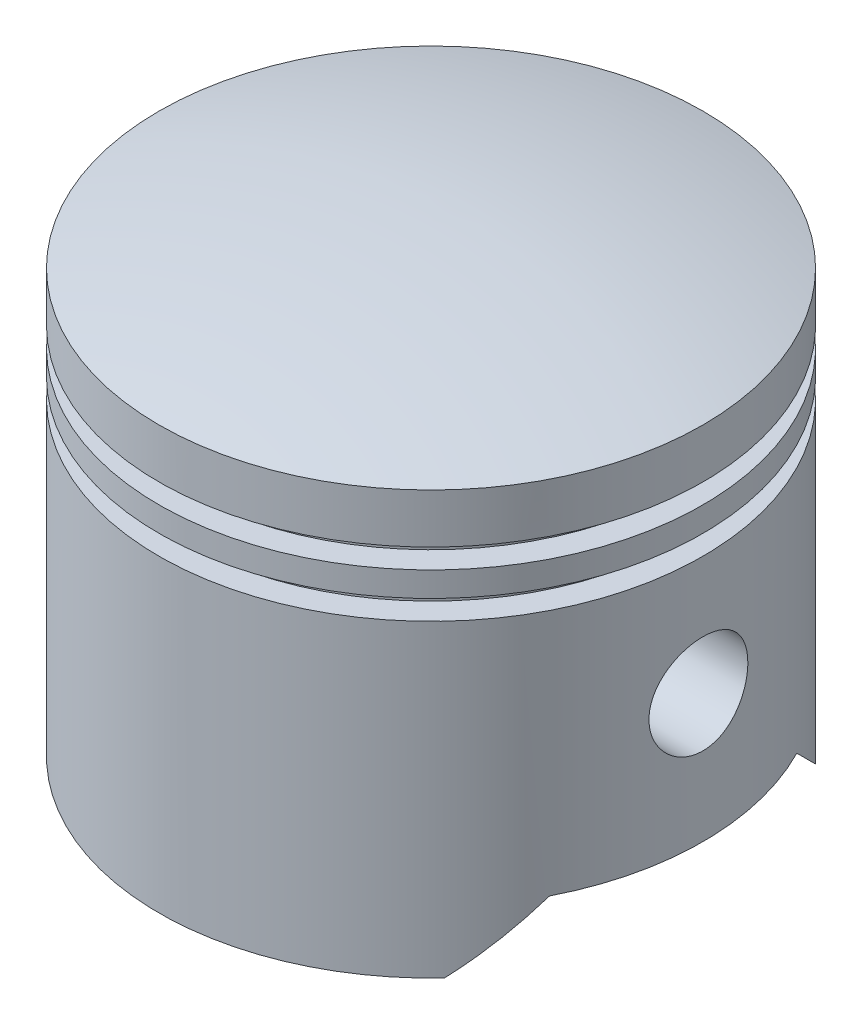
SolidWorks part; units mm, degrees
ref_plane "前视基准面" through (0, 0, 0) normal (0, 0, 1) x (1, 0, 0)
ref_plane "上视基准面" through (0, 0, 0) normal (0, 1, 0) x (1, 0, 0)
ref_plane "右视基准面" through (0, 0, 0) normal (1, 0, 0) x (0, 0, -1)
other "Configuration Table"
sketch "草图1" plane through (0, 0, 0) normal (0, 0, 1) x (1, 0, 0)
  line L0 (0, 40.7414) -> (0, -37.5312) construction
  line L1 (-34.875, 0) -> (35, 0) construction
  line L2 (-22, 9.6331) -> (-22, -15.3669)
  line L3 (-22, -15.3669) -> (0, -15.3669)
  line L4 (-22, 9.6331) -> (-20, 9.6331)
  line L5 (-20, 9.6331) -> (-20, 11.2331)
  line L6 (-20, 11.2331) -> (-22, 11.2331)
  line L7 (-22, 11.2331) -> (-22, 13.2331)
  line L8 (-22, 13.2331) -> (-20, 13.2331)
  line L9 (-20, 13.2331) -> (-20, 14.8331)
  line L10 (-20, 14.8331) -> (-22, 14.8331)
  line L11 (-22, 14.8331) -> (-22, 18.8331)
  line L12 (0, 22) -> (0, -15.3669)
  arc A1 (-22, 18.8331) -> (0, 22) centre (0, -56) cw
  dimension "D6" = 78
  dimension "D1" = 2
  dimension "D2" = 4
  dimension "D3" = 2
  dimension "D4" = 1.6
  dimension "D5" = 1.6
  dimension "D7" = 25
  dimension "D8" = 44
  dimension "D9" = 22
  dimension "D10" = 2
  dimension "D11" = 2
  dimension "D12" = 2
revolve "旋转3" add sketch "草图1" angle 360 about L12
sketch "草图4" plane through (0, 0, 0) normal (1, 0, 0) x (0, 0, -1)
  line L0 (0, 24.7947) -> (0, -19.6691) construction
  line L1 (-15, -15.3669) -> (-10, -10.3669)
  line L2 (-22, -15.3669) -> (22, -15.3669) construction
  line L3 (-10, -10.3669) -> (10, -10.3669)
  line L4 (15, -15.3669) -> (10, -10.3669)
  line L5 (-15, -15.3669) -> (15, -15.3669)
  circle A0 centre (0, 0) radius 4
  point P11 (0, -10.3669)
  dimension "D1" = 8
  dimension "D2" = 30
  dimension "D3" = 45
  dimension "D4" = 5
extrude "切除-拉伸2" cut sketch "草图4" against normal through all both and the other way through all contours A0 | L5 L4 L3 L1
sketch "草图6" plane through (0, -15.3669, 0) normal (0, -1, 0) x (1, 0, 0)
  circle A0 centre (0, 0) radius 20
  dimension "D1" = 40
extrude "切除-拉伸3" cut sketch "草图6" against normal up to surface (5 mm away) up to face at (0, -10.3669, 0)
sketch "草图7" plane through (0, -10.3669, 0) normal (0, -1, 0) x (1, 0, 0)
  line L0 (0, 22.4783) -> (0, -25.2558) construction
  line L3 (-35.2351, 0) -> (38.9253, 0) construction
sketch "草图8" plane through (0, 0, 0) normal (1, 0, 0) x (0, 0, -1)
  line L0 (-16, 17.2735) -> (-16, -10.3669)
  line L1 (-22.4783, -10.3669) -> (25.2558, -10.3669) construction
  line L2 (-16, -10.3669) -> (16, -10.3669)
  line L3 (-6, -10.3669) -> (6, -10.3669) construction
  line L4 (0, -10.3669) -> (0, 29.2615) construction
  line L5 (16, 17.2735) -> (16, -10.3669)
  arc A2 (21.1538, 15.9549) -> (-21.1538, 15.9549) centre (0, -56) ccw
  arc A3 (16, 17.2735) -> (-16, 17.2735) centre (0, -56) ccw
  dimension "D2" = 32
  dimension "D1" = 3
extrude "切除-拉伸4" cut sketch "草图8" against normal mid plane 12
sketch "草图9" plane through (0, -10.3669, 0) normal (0, -1, 0) x (1, 0, 0)
  line L0 (6, 16) -> (6, -16) construction
  line L1 (-6, -16) -> (-6, 16) construction
  line L2 (6, 16) -> (6, 14.8324)
  line L3 (-6, -16) -> (-6, -14.8324)
  line L4 (-6, -16) -> (6, -16) construction
  line L5 (-6, 16) -> (6, 16) construction
  line L6 (-6, -16) -> (6, -16)
  line L7 (-6, 16) -> (6, 16)
  line L8 (-6, 14.8324) -> (-6, 16)
  line L9 (6, -14.8324) -> (6, -16)
  arc A0 (-6, -14.8324) -> (6, -14.8324) centre (0, 0) ccw
  arc A1 (6, 14.8324) -> (-6, 14.8324) centre (0, 0) ccw
  line M14 (6, -16) -> (-6, -16)
  line M15 (-6, -16) -> (-6, 16)
  line M16 (-6, 16) -> (6, 16)
  line M17 (6, 16) -> (6, -16)
  dimension "D1" = 32
extrude "凸台-拉伸1" add sketch "草图9" against normal up to surface (27.8856 mm away) contours A0 M14 M17 | A0 L6 M15 | A1 M16 M15 | A1 L7 M17
